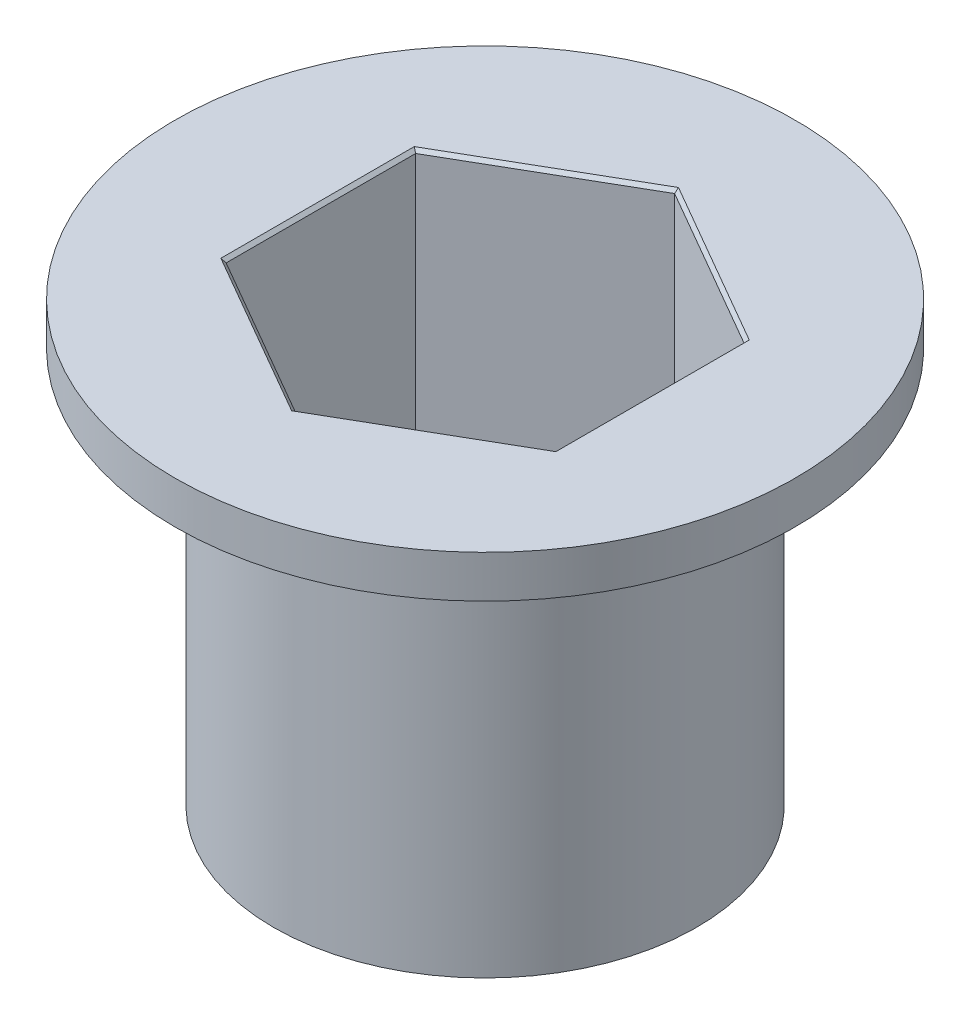
SolidWorks part; units mm, degrees
ref_plane "Front Plane" through (0, 0, 0) normal (0, 0, 1) x (1, 0, 0)
ref_plane "Top Plane" through (0, 0, 0) normal (0, 1, 0) x (1, 0, 0)
ref_plane "Right Plane" through (0, 0, 0) normal (1, 0, 0) x (0, 0, -1)
sketch "Sketch1" plane through (0, 0, 0) normal (0, 1, 0) x (1, 0, 0)
  line L1 (0, 5.6898) -> (-4.9275, 2.8449)
  line L2 (-4.9275, 2.8449) -> (-4.9275, -2.8449)
  line L3 (-4.9275, -2.8449) -> (0, -5.6898)
  line L4 (0, -5.6898) -> (4.9275, -2.8449)
  line L5 (4.9275, -2.8449) -> (4.9275, 2.8449)
  line L6 (4.9275, 2.8449) -> (0, 5.6898)
  circle A0 centre (0, 0) radius 6.35
  circle A1 centre (0, 0) radius 4.9275 construction
  dimension "D1" = 12.7
  dimension "D2" = 9.855
extrude "Boss-Extrude1" add sketch "Sketch1" along normal blind 11.8872
sketch "Sketch2" plane through (0, 11.8872, 0) normal (0, 1, 0) x (1, 0, 0)
  line L0 (0, 5.6898) -> (-4.9275, 2.8449) construction
  line L1 (-4.9275, 2.8449) -> (-4.9275, -2.8449) construction
  line L2 (4.9275, 2.8449) -> (0, 5.6898) construction
  line L3 (4.9275, -2.8449) -> (4.9275, 2.8449) construction
  line L4 (0, -5.6898) -> (4.9275, -2.8449) construction
  line L5 (-4.9275, -2.8449) -> (0, -5.6898) construction
  line L6 (0, 5.6898) -> (-4.9275, 2.8449)
  line L7 (-4.9275, 2.8449) -> (-4.9275, -2.8449)
  line L8 (4.9275, 2.8449) -> (0, 5.6898)
  line L9 (4.9275, -2.8449) -> (4.9275, 2.8449)
  line L10 (0, -5.6898) -> (4.9275, -2.8449)
  line L11 (-4.9275, -2.8449) -> (0, -5.6898)
  circle A0 centre (0, 0) radius 9.3086
extrude "Boss-Extrude2" add sketch "Sketch2" along normal blind 1.27
chamfer "Chamfer1" distance 0.1 angle 45 6 edges at (-2.4637, 0, -4.2673) (2.4637, 0, -4.2673) (4.9275, 0, 0) (2.4637, 0, 4.2673) (-4.9275, 0, 0) (-2.4637, 0, 4.2673)
chamfer "Chamfer2" distance 0.1 angle 45 6 edges at (-2.4637, 13.1572, 4.2673) (2.4637, 13.1572, 4.2673) (4.9275, 13.1572, 0) (2.4637, 13.1572, -4.2673) (-4.9275, 13.1572, 0) (-2.4637, 13.1572, -4.2673)
